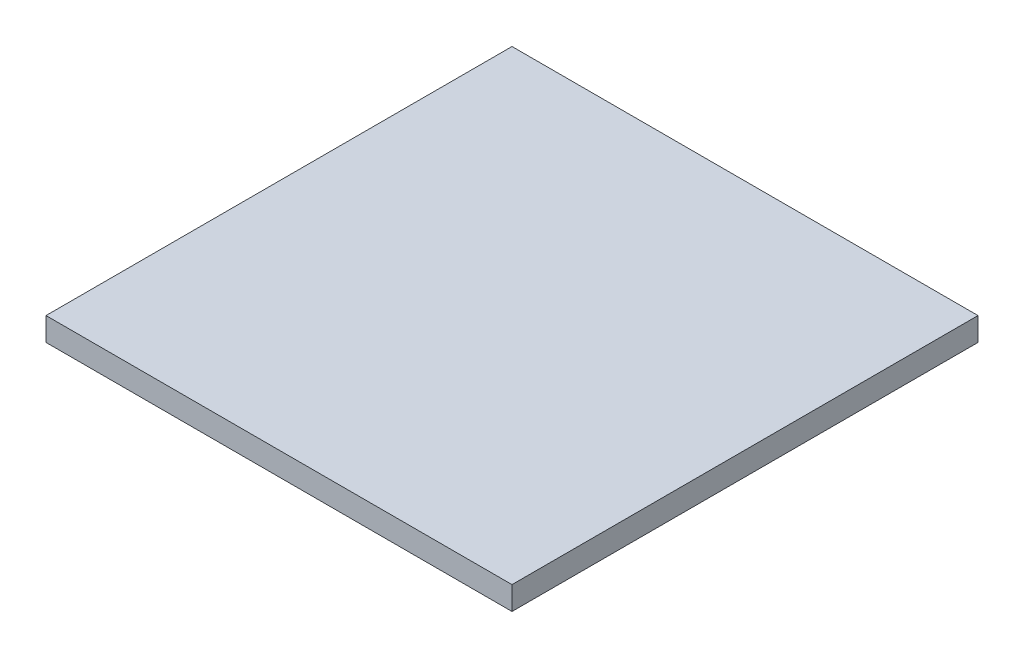
SolidWorks part; units mm, degrees
ref_plane "Front Plane" through (0, 0, 0) normal (0, 0, 1) x (1, 0, 0)
ref_plane "Top Plane" through (0, 0, 0) normal (0, 1, 0) x (1, 0, 0)
ref_plane "Right Plane" through (0, 0, 0) normal (1, 0, 0) x (0, 0, -1)
sketch "Sketch2" plane through (0, 0, 0) normal (0, 1, 0) x (1, 0, 0)
  line L1 (-200, 200) -> (200, 200)
  line L2 (-200, 200) -> (-200, -200)
  line L3 (-200, -200) -> (200, -200)
  line L4 (200, 200) -> (200, -200)
  line L5 (-200, 200) -> (200, -200) construction
  line L6 (-200, -200) -> (200, 200) construction
  point P0 (0, 0)
  dimension "D1" = 400
  dimension "D2" = 400
extrude "Boss-Extrude1" add sketch "Sketch2" along normal blind 20
